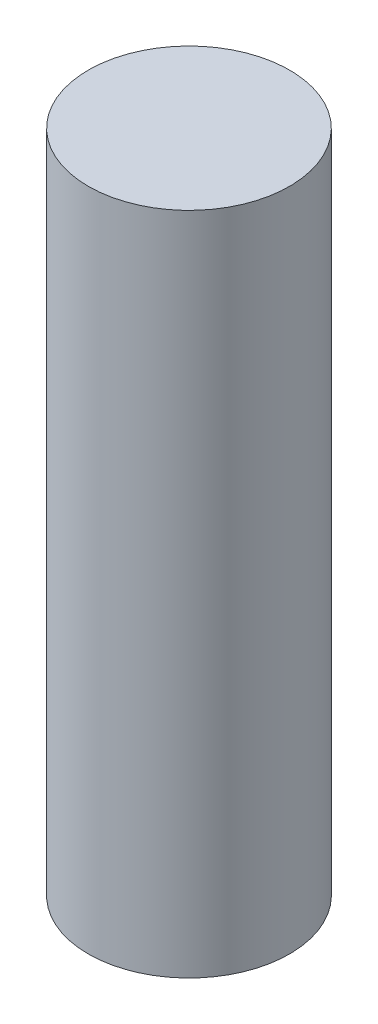
SolidWorks part; units mm, degrees
ref_plane "Front Plane" through (0, 0, 0) normal (0, 0, 1) x (1, 0, 0)
ref_plane "Top Plane" through (0, 0, 0) normal (0, 1, 0) x (1, 0, 0)
ref_plane "Right Plane" through (0, 0, 0) normal (1, 0, 0) x (0, 0, -1)
sketch "Sketch1" plane through (0, 0, 0) normal (0, 1, 0) x (1, 0, 0)
  circle A0 centre (0, 0) radius 7.5
  dimension "D1" = 15
sketch "Sketch3" plane through (0, 0, 0) normal (0, 0, 1) x (1, 0, 0)
  line L0 (0, 0) -> (0, 49.5261)
  line L1 (0, 15) -> (0, 0) construction
sweep "Sweep2" add profiles "Sketch1" path "Sketch3"
